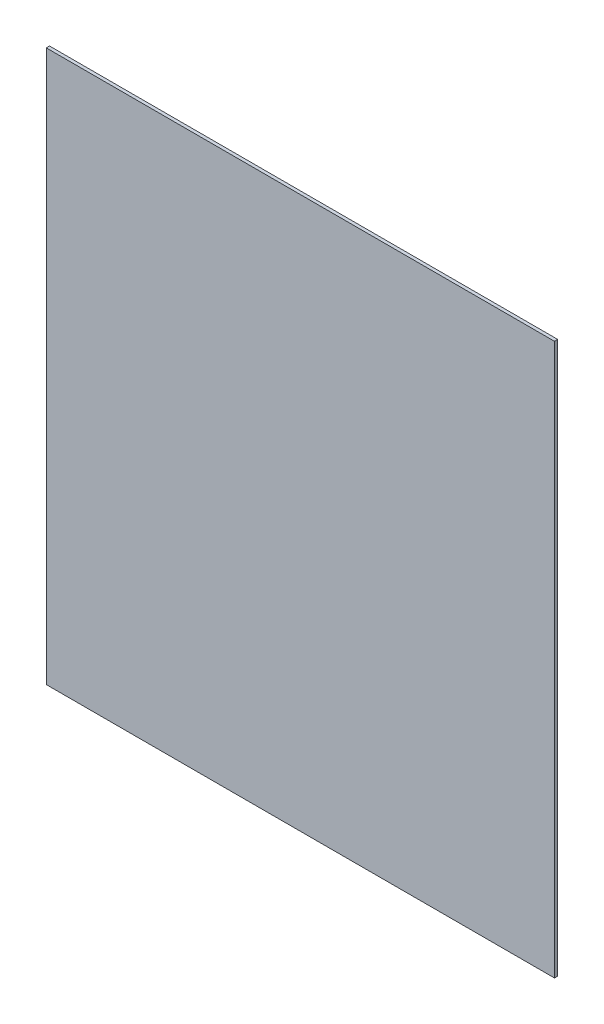
SolidWorks part; units mm, degrees
ref_plane "Front Plane" through (0, 0, 0) normal (0, 0, 1) x (1, 0, 0)
ref_plane "Top Plane" through (0, 0, 0) normal (0, 1, 0) x (1, 0, 0)
ref_plane "Right Plane" through (0, 0, 0) normal (1, 0, 0) x (0, 0, -1)
sketch "Sketch1" plane through (0, 0, 0) normal (0, 0, 1) x (1, 0, 0)
  line L1 (235, 255) -> (-235, 255)
  line L2 (235, 255) -> (235, -255)
  line L3 (235, -255) -> (-235, -255)
  line L4 (-235, 255) -> (-235, -255)
  line L5 (235, 255) -> (-235, -255) construction
  line L6 (235, -255) -> (-235, 255) construction
  point P0 (0, 0)
  dimension "D1" = 510
  dimension "D2" = 470
extrude "Boss-Extrude1" add sketch "Sketch1" along normal blind 3
